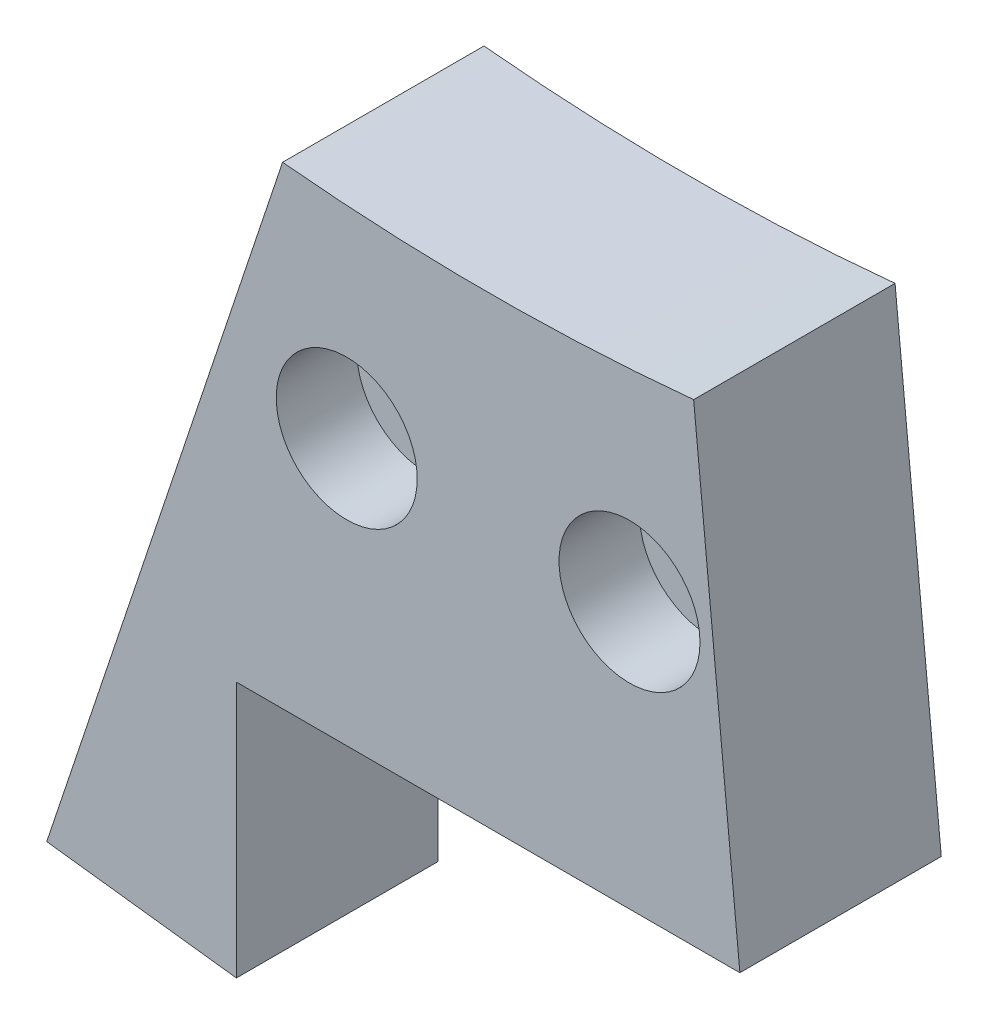
SolidWorks part; units mm, degrees
ref_plane "Plan de face" through (0, 0, 0) normal (0, 0, 1) x (1, 0, 0)
ref_plane "Plan de dessus" through (0, 0, 0) normal (0, 1, 0) x (1, 0, 0)
ref_plane "Plan de droite" through (0, 0, 0) normal (1, 0, 0) x (0, 0, -1)
sketch "Esquisse1" plane through (0, 0, 0) normal (0, 0, 1) x (1, 0, 0)
  line L0 (0, 0) -> (0, -128) construction
  line L1 (0, 0) -> (-10.2054, -104.5029) construction
  line L2 (0, 0) -> (10.2054, -104.5029) construction
  line L3 (-12.5, -128) -> (12.5, -128)
  line L4 (-10.2054, -104.5029) -> (-12.5, -128)
  line L5 (10.2054, -104.5029) -> (12.5, -128)
  arc A1 (10.2054, -104.5029) -> (-10.2054, -104.5029) centre (0, 0) cw
  point P1 (0, -105)
  point P8 (0, -128)
  dimension "D1" = 105
  dimension "D2" = 128
  dimension "D3" = 25
extrude "Boss.-Extru.1" add sketch "Esquisse1" along normal blind 10
sketch "Esquisse2" plane through (0, -128, 0) normal (0, -1, 0) x (1, 0, 0)
  line L0 (-4.75, 6) -> (4.75, 6) construction
  line L1 (-12.5, 10) -> (12.5, 10) construction
  circle A0 centre (-4.75, 6) radius 1.025
  circle A1 centre (4.75, 6) radius 1.025
  point P4 (0, 6)
  point P7 (0, 10)
  dimension "D1" = 2.05
  dimension "D2" = 9.5
  dimension "D3" = 4
extrude "Enlèv. mat.-Extru.1" cut sketch "Esquisse2" against normal blind 8
sketch "Esquisse3" plane through (0, 0, 10) normal (0, 0, 1) x (1, 0, 0)
  line L0 (0, -105) -> (0, -128) construction
  line L1 (-12.5, -128) -> (12.5, -128) construction
  line L2 (-7.0206, -114.7855) -> (0, 0) construction
  line L3 (0, 0) -> (7.0206, -114.7855) construction
  arc A0 (7.0206, -114.7855) -> (-7.0206, -114.7855) centre (0, 0) cw construction
  circle A1 centre (-7.0206, -114.7855) radius 1.75
  circle A2 centre (7.0206, -114.7855) radius 1.75
  arc A3 (-10.2054, -104.5029) -> (10.2054, -104.5029) centre (0, 0) ccw construction
  point P13 (0, -115)
  dimension "D1" = 115
  dimension "D2" = 3.5
  dimension "D3" = 7
extrude "Enlèv. mat.-Extru.2" cut sketch "Esquisse3" against normal up to next
sketch "Esquisse4" plane through (0, 0, 10) normal (0, 0, 1) x (1, 0, 0)
  circle A0 centre (-7.0206, -114.7855) radius 3.5
  circle A1 centre (7.0206, -114.7855) radius 3.5
  circle M4 centre (7.0206, -114.7855) radius 1.75
  dimension "D1" = 7
extrude "Enlèv. mat.-Extru.3" cut sketch "Esquisse4" against normal blind 4 contours A1 M4 | A0
sketch "Esquisse5" plane through (0, 0, 10) normal (0, 0, 1) x (1, 0, 0)
  line L0 (0, 0) -> (-17.208, -140.1475) construction
  line L1 (0, -105) -> (0, 0) construction
  line L2 (-12.5, -140.7256) -> (-21.9159, -139.5695)
  line L3 (-12.5, -140.7256) -> (-12.5, -128)
  line L4 (-21.9159, -139.5695) -> (-10.2054, -104.5029)
  line L5 (-10.2054, -104.5029) -> (-12.5, -128)
  line L6 (-12.5, -128) -> (12.5, -128) construction
  arc A0 (-10.2054, -104.5029) -> (10.2054, -104.5029) centre (0, 0) ccw construction
  point P6 (-17.208, -140.1475)
  dimension "D1" = 141.2
  dimension "D3" = 7
extrude "Boss.-Extru.2" add sketch "Esquisse5" against normal blind 10
sketch "Esquisse6" plane through (-17.208, -140.1475, 0) normal (-0.1219, -0.9925, 0) x (0.9925, -0.1219, 0)
  line L0 (-4.7433, 10) -> (4.7433, 0) construction
  circle A0 centre (0, 5) radius 2.75
  dimension "D1" = 5.5
extrude "Enlèv. mat.-Extru.4" cut sketch "Esquisse6" against normal blind 2
